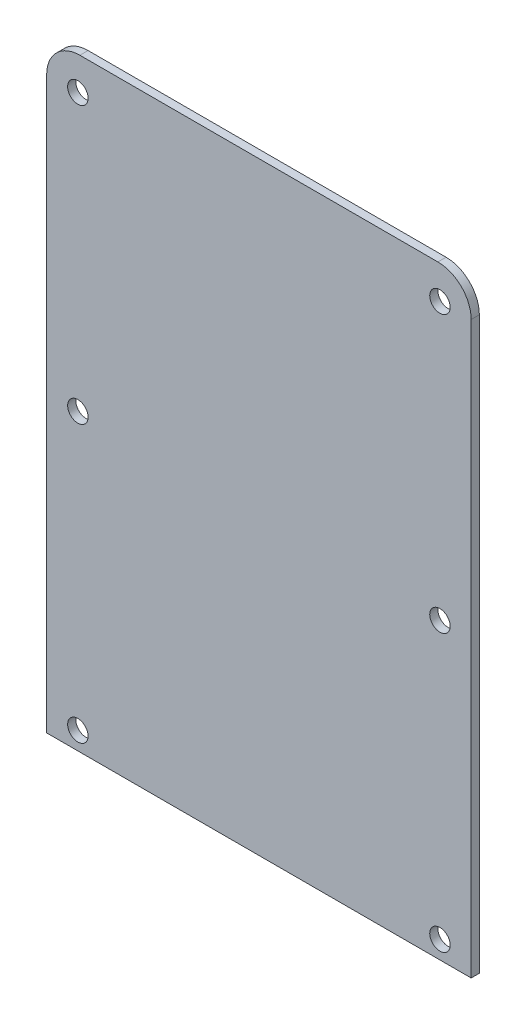
SolidWorks part; units mm, degrees
ref_plane "前视基准面" through (0, 0, 0) normal (0, 0, 1) x (1, 0, 0)
ref_plane "上视基准面" through (0, 0, 0) normal (0, 1, 0) x (1, 0, 0)
ref_plane "右视基准面" through (0, 0, 0) normal (1, 0, 0) x (0, 0, -1)
sketch "草图1" plane through (0, 0, 0) normal (0, 0, 1) x (1, 0, 0)
  line L1 (-41.75, 66.25) -> (-6.75, 66.25)
  line L2 (-45, 63) -> (-45, 7.25)
  line L3 (-45, 7.25) -> (-3.5, 7.25)
  line L4 (-3.5, 63) -> (-3.5, 7.25)
  arc A0 (-6.75, 66.25) -> (-3.5, 63) centre (-6.75, 63) cw
  arc A1 (-41.75, 66.25) -> (-45, 63) centre (-41.75, 63) ccw
  point P7 (-3.5, 66.25)
  point P10 (-45, 66.25)
  dimension "D3" = 3.25
  dimension "D4" = 3.25
  dimension "D1" = 41.5
  dimension "D2" = 59
extrude "凸台-拉伸1" add sketch "草图1" along normal blind 0.8 contours L2 L3 L4 A0 L1 A1
sketch "草图2" plane through (0, 0, 0.8) normal (0, 0, 1) x (1, 0, 0)
  line L0 (-45, 63) -> (-45, 7.25) construction
  line L1 (-41.75, 66.25) -> (-6.75, 66.25) construction
  line L2 (-41.95, 63) -> (-41.95, 36) construction
  line L3 (-24.25, -943.2655) -> (-24.25, 49056.7345) construction
  line L4 (-3.5, 63) -> (-3.5, 7.25) construction
  circle A0 centre (-41.95, 63) radius 1
  circle A1 centre (-41.95, 36) radius 1
  circle A2 centre (-41.95, 9) radius 1
  circle A3 centre (-6.55, 9) radius 1
  circle A4 centre (-6.55, 36) radius 1
  circle A5 centre (-6.55, 63) radius 1
  dimension "D1" = 2
  dimension "D2" = 3.05
  dimension "D3" = 3.25
  dimension "D5" = 27
  dimension "D4" = 3
extrude "切除-拉伸1" cut sketch "草图2" against normal through all
